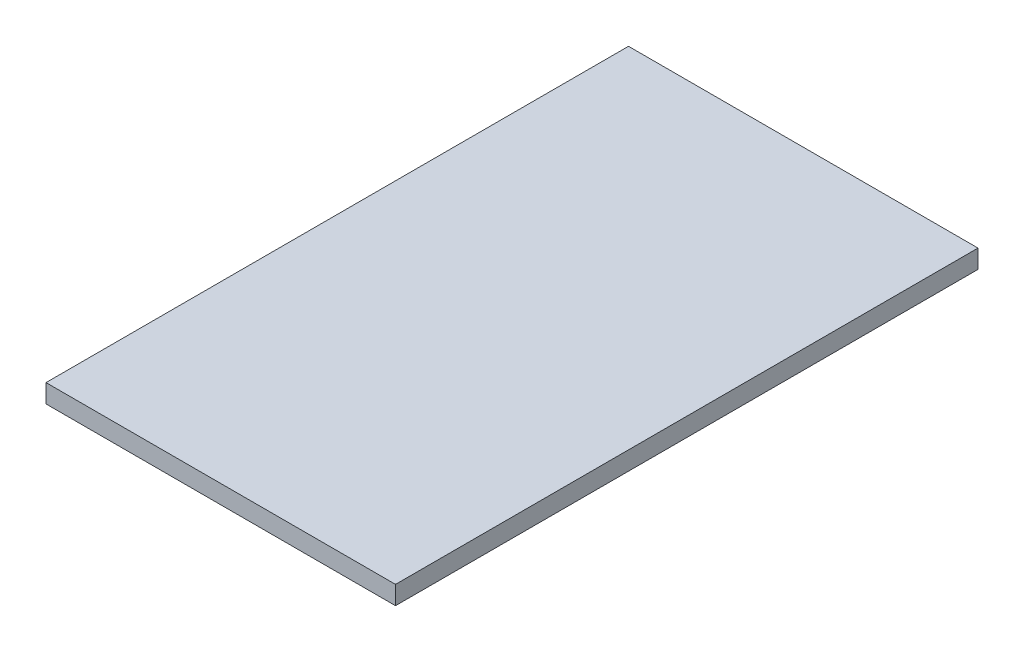
SolidWorks part; units mm, degrees
ref_plane "Front Plane" through (0, 0, 0) normal (0, 0, 1) x (1, 0, 0)
ref_plane "Top Plane" through (0, 0, 0) normal (0, 1, 0) x (1, 0, 0)
ref_plane "Right Plane" through (0, 0, 0) normal (1, 0, 0) x (0, 0, -1)
sketch "Sketch1" plane through (0, 0, 0) normal (0, 0, 1) x (1, 0, 0)
  line L1 (-15, 0.7937) -> (15, 0.7937)
  line L2 (-15, 0.7937) -> (-15, -0.7937)
  line L3 (-15, -0.7937) -> (15, -0.7937)
  line L4 (15, 0.7937) -> (15, -0.7937)
  line L5 (-15, 0.7937) -> (15, -0.7937) construction
  line L6 (-15, -0.7937) -> (15, 0.7937) construction
  point P0 (0, 0)
  dimension "D1" = 1.5875
  dimension "D2" = 30
extrude "Boss-Extrude1" add sketch "Sketch1" along normal blind 50
